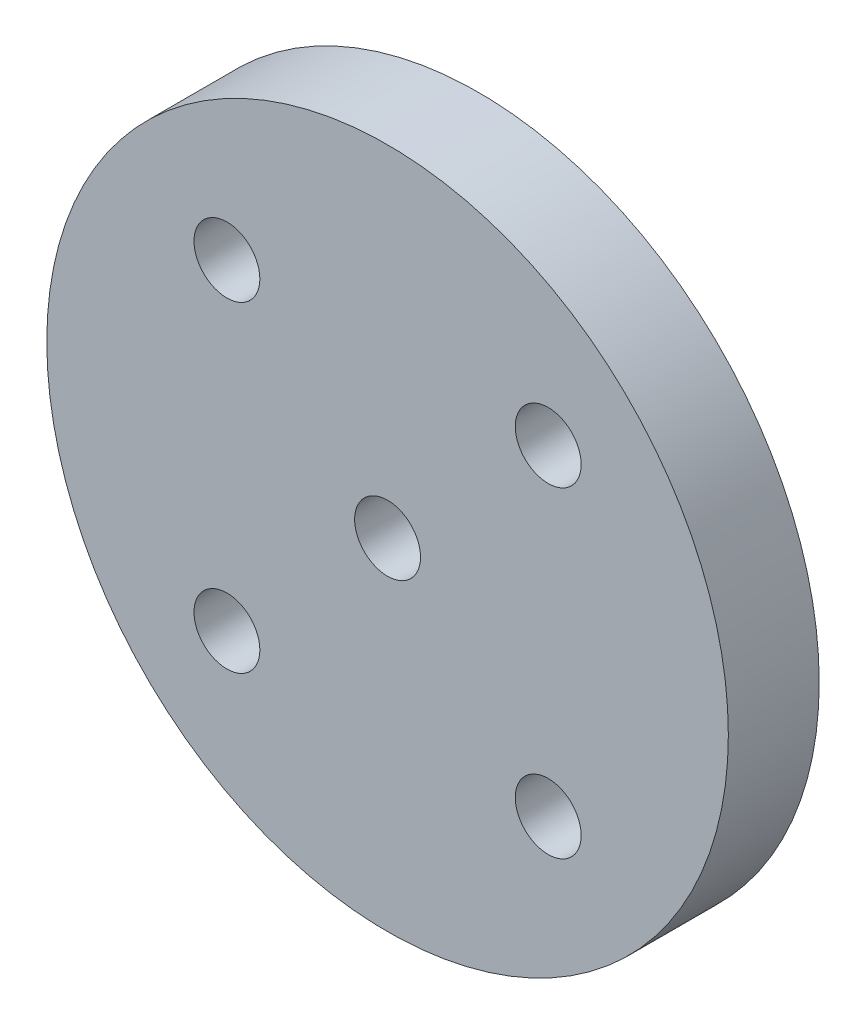
SolidWorks part; units mm, degrees
ref_plane "前视基准面" through (0, 0, 0) normal (0, 0, 1) x (1, 0, 0)
ref_plane "上视基准面" through (0, 0, 0) normal (0, 1, 0) x (1, 0, 0)
ref_plane "右视基准面" through (0, 0, 0) normal (1, 0, 0) x (0, 0, -1)
other "Configuration Table"
sketch "草图1" plane through (0, 0, 0) normal (0, 0, 1) x (1, 0, 0)
  line L0 (0, 0) -> (-7.0711, 7.0711) construction
  line L1 (0, 0) -> (7.0711, 7.0711) construction
  line L2 (0, 0) -> (7.0711, -7.0711) construction
  line L3 (0, 0) -> (-7.0711, -7.0711) construction
  line L4 (0, 0) -> (0, -4.7703) construction
  circle A0 centre (0, 0) radius 15
  circle A1 centre (0, 0) radius 1.45
  circle A2 centre (-7.0711, -7.0711) radius 1.45
  circle A3 centre (-7.0711, 7.0711) radius 1.45
  circle A4 centre (7.0711, 7.0711) radius 1.45
  circle A5 centre (7.0711, -7.0711) radius 1.45
  dimension "D1" = 30
  dimension "D2" = 2.9
  dimension "D11" = 2.9
  dimension "D3" = 45
  dimension "D4" = 45
  dimension "D5" = 90
  dimension "D6" = 90
  dimension "D7" = 10
  dimension "D8" = 10
  dimension "D9" = 10
  dimension "D10" = 10
extrude "凸台-拉伸1" add sketch "草图1" along normal blind 4
